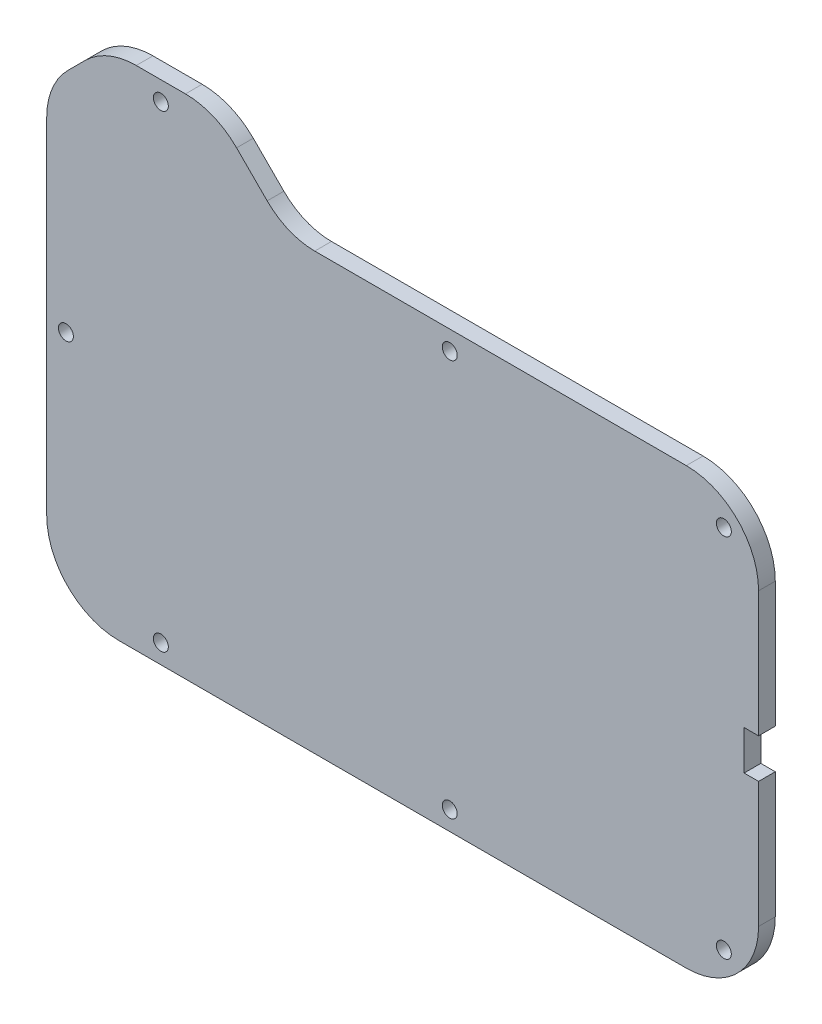
SolidWorks part; units mm, degrees
ref_plane "Front Plane" through (0, 0, 0) normal (0, 0, 1) x (1, 0, 0)
ref_plane "Top Plane" through (0, 0, 0) normal (0, 1, 0) x (1, 0, 0)
ref_plane "Right Plane" through (0, 0, 0) normal (1, 0, 0) x (0, 0, -1)
sketch "Sketch1" plane through (0, 0, 0) normal (0, 0, 1) x (1, 0, 0)
  line L51 (143.9081, 20.4605) -> (143.9081, 75.7605) construction
  line L52 (130.0581, 89.6105) -> (59.3752, 89.6105) construction
  line L53 (50.3949, 93.3302) -> (44.5712, 99.1539) construction
  line L54 (34.7778, 103.2105) -> (25.4148, 103.2105) construction
  line L55 (15.6214, 99.1539) -> (12.3411, 95.8737) construction
  line L56 (8.2846, 86.0802) -> (8.2846, 20.4605) construction
  line L57 (22.1346, 6.6105) -> (130.0581, 6.6105) construction
  line L58 (143.8081, 20.4605) -> (143.8081, 44.3605)
  line L59 (130.0581, 89.5105) -> (59.3752, 89.5105)
  line L60 (50.3242, 93.2595) -> (44.5005, 99.0832)
  line L61 (34.7778, 103.1105) -> (25.4148, 103.1105)
  line L62 (15.6921, 99.0832) -> (12.4118, 95.803)
  line L63 (8.3846, 86.0802) -> (8.3846, 20.4605)
  line L64 (22.1346, 6.7105) -> (130.0581, 6.7105)
  line L65 (143.8081, 48.1105) -> (141.0581, 48.1105) construction
  line L66 (141.0581, 44.3605) -> (141.0581, 51.8605)
  line L67 (141.0581, 51.8605) -> (143.8081, 51.8605)
  line L68 (141.0581, 44.3605) -> (143.8081, 44.3605)
  line L69 (143.8081, 51.8605) -> (143.8081, 75.7605)
  line L70 (143.8081, 51.8605) -> (143.8081, 44.3605) construction
  arc A71 (130.0581, 6.6105) -> (143.9081, 20.4605) centre (130.0581, 20.4605) ccw construction
  arc A72 (143.9081, 75.7605) -> (130.0581, 89.6105) centre (130.0581, 75.7605) ccw construction
  arc A73 (50.3949, 93.3302) -> (59.3752, 89.6105) centre (59.3752, 102.3105) ccw construction
  arc A74 (44.5712, 99.1539) -> (34.7778, 103.2105) centre (34.7778, 89.3605) ccw construction
  arc A75 (25.4148, 103.2105) -> (15.6214, 99.1539) centre (25.4148, 89.3605) ccw construction
  arc A76 (12.3411, 95.8737) -> (8.2846, 86.0802) centre (22.1346, 86.0802) ccw construction
  arc A77 (8.2846, 20.4605) -> (22.1346, 6.6105) centre (22.1346, 20.4605) ccw construction
  circle A78 centre (12.0346, 52.4704) radius 1.425
  circle A79 centre (30.0963, 99.4605) radius 1.425
  circle A80 centre (85.0537, 85.8605) radius 1.425
  circle A81 centre (137.1998, 82.9023) radius 1.425
  circle A82 centre (137.1998, 13.3187) radius 1.425
  circle A83 centre (85.0537, 10.3605) radius 1.425
  circle A84 centre (30.0963, 10.3605) radius 1.425
  arc A85 (143.8081, 75.7605) -> (130.0581, 89.5105) centre (130.0581, 75.7605) ccw
  arc A86 (50.3242, 93.2595) -> (59.3752, 89.5105) centre (59.3752, 102.3105) ccw
  arc A87 (44.5005, 99.0832) -> (34.7778, 103.1105) centre (34.7778, 89.3605) ccw
  arc A88 (25.4148, 103.1105) -> (15.6921, 99.0832) centre (25.4148, 89.3605) ccw
  arc A89 (12.4118, 95.803) -> (8.3846, 86.0802) centre (22.1346, 86.0802) ccw
  arc A90 (8.3846, 20.4605) -> (22.1346, 6.7105) centre (22.1346, 20.4605) ccw
  arc A91 (130.0581, 6.7105) -> (143.8081, 20.4605) centre (130.0581, 20.4605) ccw
  point P125 (141.0581, 48.1105)
extrude "Boss-Extrude1" add sketch "Sketch1" along normal blind 3.175
sketch "Sketch2" plane through (0, 0, 3.175) normal (0, 0, 1) x (1, 0, 0)
  circle A0 centre (137.1998, 82.9023) radius 2.5
  circle A1 centre (137.1998, 13.3187) radius 2.5
  circle A2 centre (85.0537, 10.3605) radius 2.5
  circle A3 centre (30.0963, 10.3605) radius 2.5
  circle A4 centre (12.0346, 52.4704) radius 2.5
  circle A5 centre (30.0963, 99.4605) radius 2.5
  circle A6 centre (85.0537, 85.8605) radius 2.5
extrude "Cut-Extrude1" [suppressed] cut sketch "Sketch2" against normal blind 0.5
sketch "Sketch3" [suppressed] plane through (0, 0, 2.675) normal (0, 0, 1) x (1, 0, 0)
  circle A0 centre (30.0963, 10.3605) radius 2.5 construction
  circle A1 centre (85.0537, 10.3605) radius 2.5
  circle A2 centre (85.0537, 10.3605) radius 2.5
  circle A3 centre (12.0346, 52.4704) radius 2.5 construction
  circle A4 centre (30.0963, 99.4605) radius 2.5 construction
  circle A5 centre (85.0537, 85.8605) radius 2.5 construction
  circle A6 centre (137.1998, 82.9023) radius 2.5 construction
  circle A7 centre (137.1998, 13.3187) radius 2.5 construction
  circle A8 centre (30.0963, 10.3605) radius 2.5
  circle A9 centre (12.0346, 52.4704) radius 2.5
  circle A10 centre (30.0963, 99.4605) radius 2.5
  circle A11 centre (85.0537, 85.8605) radius 2.5
  circle A12 centre (137.1998, 82.9023) radius 2.5
  circle A13 centre (137.1998, 13.3187) radius 2.5
  dimension "D1" = 0
extrude "Cut-Extrude2" [suppressed] cut sketch "Sketch3" against normal blind 1.2 draft 42
